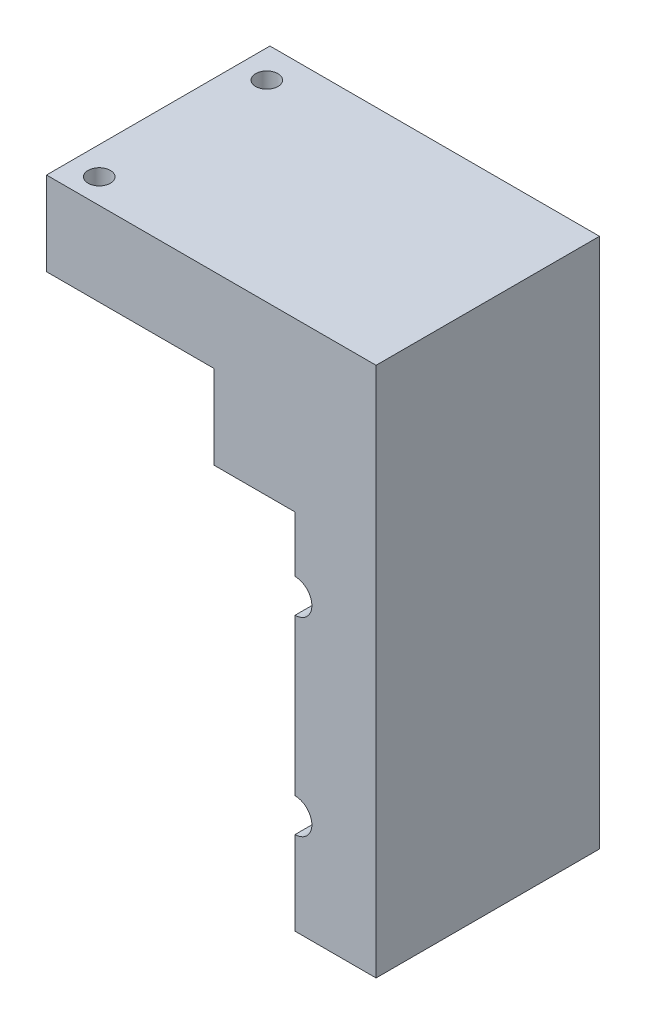
SolidWorks part; units mm, degrees
ref_plane "前视基准面" through (0, 0, 0) normal (0, 0, 1) x (1, 0, 0)
ref_plane "上视基准面" through (0, 0, 0) normal (0, 1, 0) x (1, 0, 0)
ref_plane "右视基准面" through (0, 0, 0) normal (1, 0, 0) x (0, 0, -1)
sketch "草图3" plane through (0, 0, 0) normal (0, 0, 1) x (1, 0, 0)
  line L1 (0, 0) -> (29, 0)
  line L2 (0, 0) -> (0, 95)
  line L3 (0, 95) -> (29, 95)
  line L4 (29, 0) -> (29, 95)
extrude "凸台-拉伸1" add sketch "草图3" along normal blind 40
sketch "草图4" plane through (0, 0, 40) normal (0, 0, 1) x (1, 0, 0)
  line L0 (0, 0) -> (29, 0) construction
  circle A2 centre (14.5, 52) radius 3.005
  circle A3 centre (14.5, 18) radius 3.005
  circle A4 centre (14.5, 52) radius 3.025
  circle A5 centre (14.5, 18) radius 3.025
  dimension "D1" = 34
  dimension "D2" = 18
  dimension "D3" = 0.02
  dimension "D4" = 0.02
extrude "切除-拉伸1" cut sketch "草图4" against normal through all contours A2 | A3
sketch "草图6" plane through (0, 0, 0) normal (-1, 0, 0) x (0, 0, 1)
  line L0 (40, 95) -> (40, 0) construction
  line L1 (0, 95) -> (40, 95)
  line L2 (0, 95) -> (0, 80)
  line L3 (0, 80) -> (40, 80)
  line L4 (40, 95) -> (40, 80)
extrude "凸台-拉伸3" add sketch "草图6" along normal blind 30
sketch "草图7" plane through (0, 0, 40) normal (0, 0, 1) x (1, 0, 0)
  line L0 (0, 80) -> (0, 0) construction
  line L1 (0, 65) -> (14.5, 65)
  line L2 (0, 65) -> (0, 0)
  line L3 (0, 0) -> (14.5, 0)
  line L4 (14.5, 65) -> (14.5, 0)
  line L5 (0, 0) -> (29, 0) construction
extrude "切除-拉伸2" cut sketch "草图7" against normal through all
sketch "草图9" plane through (14.5, 0, 0) normal (-1, 0, 0) x (0, 0, 1)
  line L0 (0, 55.005) -> (0, 65) construction
  circle A0 centre (5, 60.0025) radius 2
  circle A3 centre (35, 60.0025) radius 2
  dimension "D1" = 4
  dimension "D3" = 30
  dimension "D2" = 5
extrude "切除-拉伸4" cut sketch "草图9" against normal blind 5
sketch "草图10" plane through (14.5, 0, 0) normal (-1, 0, 0) x (0, 0, 1)
  line L0 (0, 0) -> (0, 14.995) construction
  circle A0 centre (5, 7.4975) radius 2
  circle A3 centre (35, 7.4975) radius 2
  dimension "D1" = 4
  dimension "D2" = 5
  dimension "D3" = 30
extrude "切除-拉伸5" cut sketch "草图10" against normal blind 5
sketch "草图11" plane through (14.5, 0, 0) normal (-1, 0, 0) x (0, 0, 1)
  line L0 (0, 21.005) -> (0, 48.995) construction
  circle A0 centre (5, 35) radius 2
  circle A3 centre (35, 35) radius 2
  dimension "D1" = 4
  dimension "D2" = 30
  dimension "D3" = 5
extrude "切除-拉伸6" cut sketch "草图11" against normal blind 5
sketch "草图12" plane through (0, 95, 0) normal (0, 1, 0) x (1, 0, 0)
  line L0 (-30, -40) -> (-30, 0) construction
  circle A0 centre (-25, -35.5635) radius 2
  circle A3 centre (-25, -5.5635) radius 2
  dimension "D1" = 4
  dimension "D2" = 30
  dimension "D5" = 5
extrude "切除-拉伸7" cut sketch "草图12" against normal blind 5 contours A0
